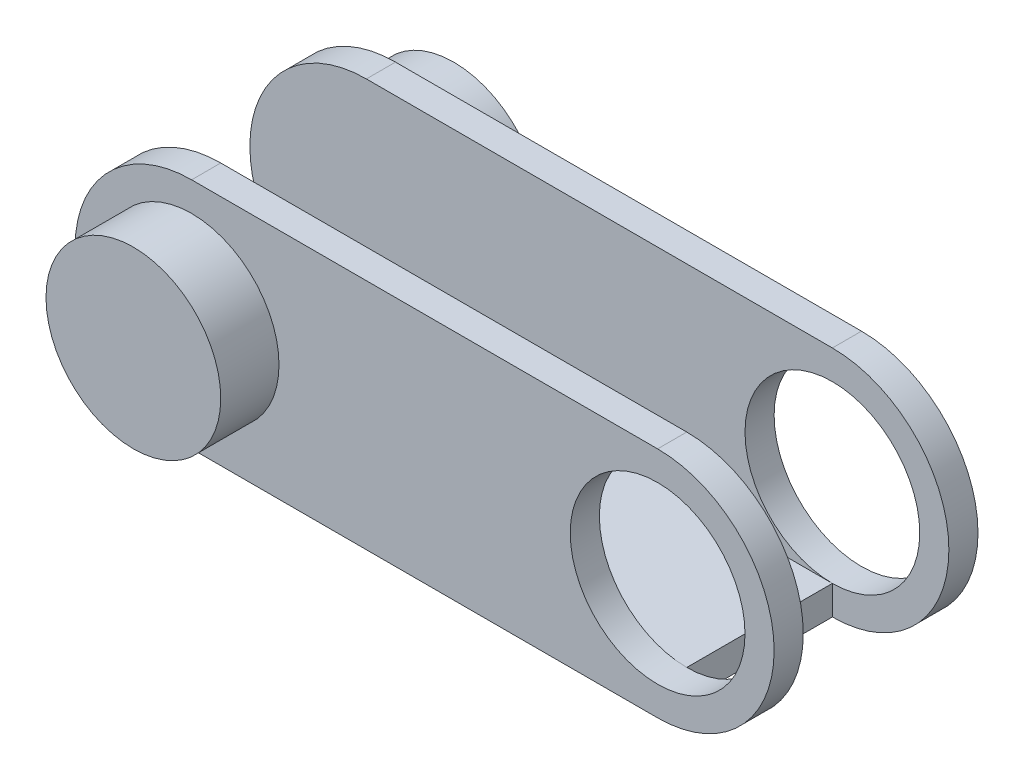
SolidWorks part; units mm, degrees
ref_plane "Front Plane" through (0, 0, 0) normal (0, 0, 1) x (1, 0, 0)
ref_plane "Top Plane" through (0, 0, 0) normal (0, 1, 0) x (1, 0, 0)
ref_plane "Right Plane" through (0, 0, 0) normal (1, 0, 0) x (0, 0, -1)
sketch "Sketch2" plane through (0, 0, 0) normal (0, 0, 1) x (1, 0, 0)
  line L0 (0, 0) -> (-160, 0) construction
  line L1 (0, -40) -> (-160, -40)
  line L2 (0, 40) -> (-160, 40)
  arc A0 (0, -40) -> (0, 40) centre (0, 0) ccw
  arc A1 (-160, 40) -> (-160, -40) centre (-160, 0) ccw
  circle A2 centre (0, 0) radius 30
  point P3 (-80, 0)
  dimension "D2" = 40
  dimension "D1" = 160
extrude "Boss-Extrude1" add sketch "Sketch2" along normal blind 10
sketch "Sketch3" plane through (0, 0, 10) normal (0, 0, 1) x (1, 0, 0)
  circle A0 centre (-160, 0) radius 30
extrude "Boss-Extrude2" add sketch "Sketch3" along normal blind 20
sketch "Sketch5" plane through (0, -40, 0) normal (0, -1, 0) x (1, 0, 0)
  line L1 (0, 0) -> (-160, 0)
  line L2 (0, 0) -> (0, -60)
  line L3 (0, -60) -> (-160, -60)
  line L4 (-160, 0) -> (-160, -60)
  dimension "D1" = 60
extrude "Boss-Extrude3" add sketch "Sketch5" against normal blind 10
ref_plane "Plane1" through (0, 0, -25) normal (0, 0, -1) x (-1, 0, 0)
mirror "Mirror1" about plane through (0, 0, -25) normal (0, 0, -1) of "Boss-Extrude2", "Boss-Extrude1"
